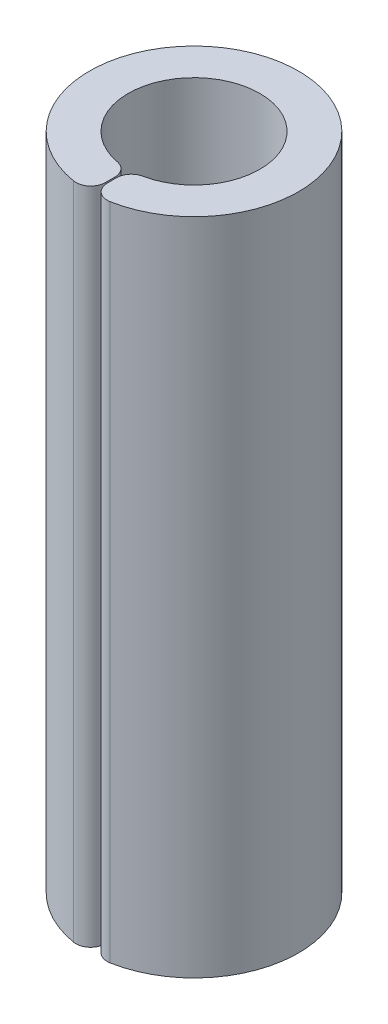
SolidWorks part; units mm, degrees
ref_plane "Front" through (0, 0, 0) normal (0, 0, 1) x (1, 0, 0)
ref_plane "Top" through (0, 0, 0) normal (0, 1, 0) x (1, 0, 0)
ref_plane "Right" through (0, 0, 0) normal (1, 0, 0) x (0, 0, -1)
sketch "Sketch1" plane through (0, 0, 0) normal (0, 1, 0) x (1, 0, 0)
  line L0 (0, 0) -> (0, -4.25) construction
  line L1 (0, 0) -> (0.0742, -4.2494) construction
  line L2 (0.0467, -2.6746) -> (0.0742, -4.2494)
  line L3 (0, -2.675) -> (0, -4.25)
  circle A0 centre (0, 0) radius 4.25 construction
  circle A1 centre (0, 0) radius 2.675 construction
  arc A2 (0.0467, -2.6746) -> (0, -2.675) centre (0, 0) ccw
  arc A3 (0.0742, -4.2494) -> (0, -4.25) centre (0, 0) ccw
  dimension "D1" = 5.35
  dimension "D2" = 8.5
  dimension "D3" = 1
extrude "Boss-Extrude1" add sketch "Sketch1" along normal blind 26.8
fillet "Fillet1" radius 0.6 4 edges at (0.0742, 13.4, 4.2494) (0, 13.4, 4.25) (0.0467, 13.4, 2.6746) (0, 13.4, 2.675)
